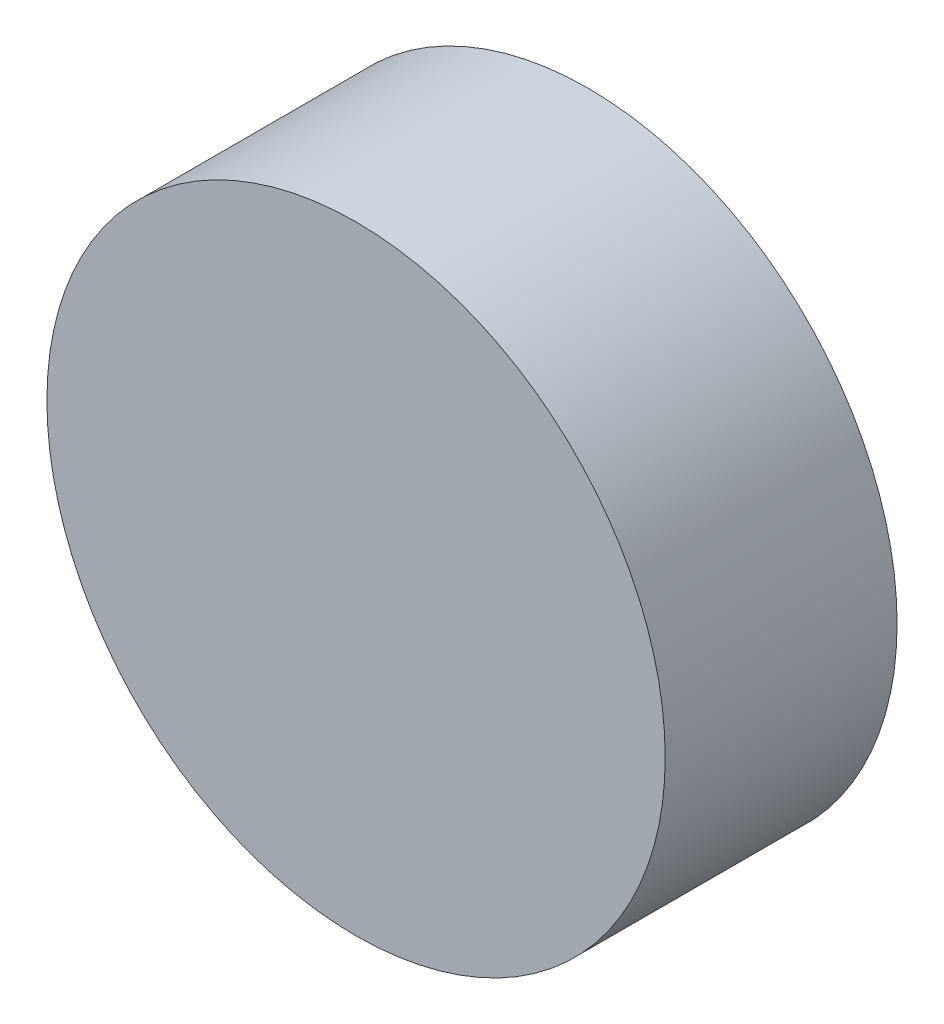
SolidWorks part; units mm, degrees
ref_plane "Front Plane" through (0, 0, 0) normal (0, 0, 1) x (1, 0, 0)
ref_plane "Top Plane" through (0, 0, 0) normal (0, 1, 0) x (1, 0, 0)
ref_plane "Right Plane" through (0, 0, 0) normal (1, 0, 0) x (0, 0, -1)
sketch "Sketch2" plane through (0, 0, 0) normal (0, 0, 1) x (1, 0, 0)
  circle A0 centre (15, 15) radius 5
extrude "Boss-Extrude1" add sketch "Sketch2" along normal blind 1
sketch "Sketch3" plane through (0, 0, 1) normal (0, 0, 1) x (1, 0, 0)
  circle A0 centre (15, 15) radius 8
  dimension "D1" = 16
extrude "Boss-Extrude2" add sketch "Sketch3" along normal blind 6
